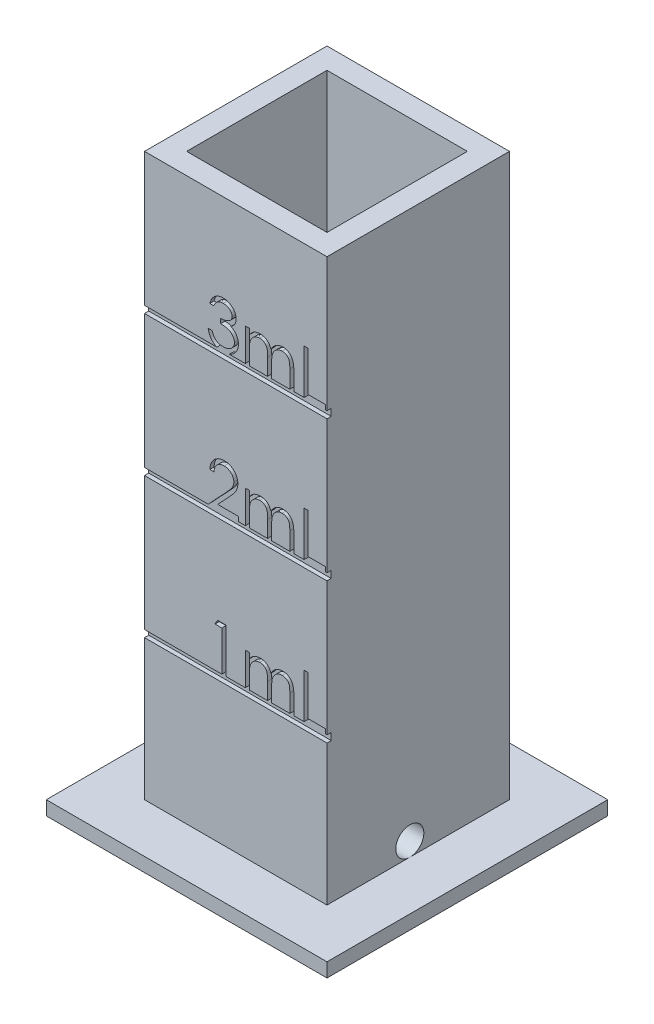
SolidWorks part; units mm, degrees
ref_plane "Front Plane" through (0, 0, 0) normal (0, 0, 1) x (1, 0, 0)
ref_plane "Top Plane" through (0, 0, 0) normal (0, 1, 0) x (1, 0, 0)
ref_plane "Right Plane" through (0, 0, 0) normal (1, 0, 0) x (0, 0, -1)
sketch "Sketch1" plane through (0, 0, 0) normal (0, 1, 0) x (1, 0, 0)
  line L0 (-6.5, 6.5) -> (6.5, 6.5)
  line L1 (-5, -5) -> (5, -5)
  line L2 (-5, -5) -> (-5, 5)
  line L3 (-5, 5) -> (5, 5)
  line L4 (5, -5) -> (5, 5)
  line L5 (-5, -5) -> (5, 5) construction
  line L6 (-5, 5) -> (5, -5) construction
  line L7 (6.5, -6.5) -> (6.5, 6.5)
  line L8 (-6.5, -6.5) -> (6.5, -6.5)
  line L9 (-6.5, -6.5) -> (-6.5, 6.5)
  point P0 (0, 0)
  dimension "D1" = 10
  dimension "D2" = 10
  dimension "D3" = 1.5
extrude "Boss-Extrude1" add sketch "Sketch1" along normal blind 40
sketch "Sketch2" plane through (0, 0, 6.5) normal (0, 0, 1) x (1, 0, 0)
  line L0 (-6.5, 40) -> (-6.5, 0) construction
  line L1 (-6.5, 10.5) -> (6.5, 10.5)
  line L2 (-6.5, 10.5) -> (-6.5, 10)
  line L3 (-6.5, 10) -> (6.5, 10)
  line L4 (6.5, 10.5) -> (6.5, 10)
  line L5 (6.5, 40) -> (6.5, 0) construction
  line L6 (-6.5, 0) -> (6.5, 0) construction
  line L7 (-6.5, 20.5) -> (6.5, 20.5)
  line L8 (-6.5, 20) -> (6.5, 20)
  line L9 (-6.5, 20.5) -> (-6.5, 20)
  line L10 (6.5, 20.5) -> (6.5, 20)
  line L11 (-6.5, 30.5) -> (6.5, 30.5)
  line L12 (-6.5, 30) -> (6.5, 30)
  line L13 (-6.5, 30.5) -> (-6.5, 30)
  line L14 (6.5, 30.5) -> (6.5, 30)
  line L15 (-6.5, 40.5) -> (6.5, 40.5)
  line L16 (-6.5, 40) -> (6.5, 40)
  line L17 (-6.5, 40.5) -> (-6.5, 40)
  line L18 (6.5, 40.5) -> (6.5, 40)
  line L19 (-6.5, 50.5) -> (6.5, 50.5)
  line L20 (-6.5, 50) -> (6.5, 50)
  line L21 (-6.5, 50.5) -> (-6.5, 50)
  line L22 (6.5, 50.5) -> (6.5, 50)
  line L23 (-6.5, 60.5) -> (6.5, 60.5)
  line L24 (-6.5, 60) -> (6.5, 60)
  line L25 (-6.5, 60.5) -> (-6.5, 60)
  line L26 (6.5, 60.5) -> (6.5, 60)
  dimension "D1" = 0.5
  dimension "D2" = 10
  dimension "D3" = 6
extrude "Cut-Extrude1" cut sketch "Sketch2" against normal blind 0.3
sketch "Sketch3" plane through (0, 0, 0) normal (0, -1, 0) x (1, 0, 0)
  line L1 (-10, -10) -> (10, -10)
  line L2 (-10, -10) -> (-10, 10)
  line L3 (-10, 10) -> (10, 10)
  line L4 (10, -10) -> (10, 10)
  line L5 (-10, -10) -> (10, 10) construction
  line L6 (-10, 10) -> (10, -10) construction
  point P0 (0, 0)
  dimension "D1" = 20
  dimension "D2" = 20
extrude "Boss-Extrude2" add sketch "Sketch3" along normal blind 1
sketch "Sketch4" plane through (6.5, 0, 0) normal (1, 0, 0) x (0, 0, -1)
  line L1 (10, -1) -> (-10, -1) construction
  circle A0 centre (-0.6013, 1) radius 1
  dimension "D1" = 2
  dimension "D2" = 2
extrude "Cut-Extrude3" cut sketch "Sketch4" against normal blind 21 and the other way blind 5
sketch "Sketch5" plane through (0, 0, 6.5) normal (0, 0, 1) x (1, 0, 0)
  text T0 "1mL"
  text T1 "2mL"
  text T2 "3mL"
extrude "Cut-Extrude4" cut sketch "Sketch5" against normal blind 0.3
